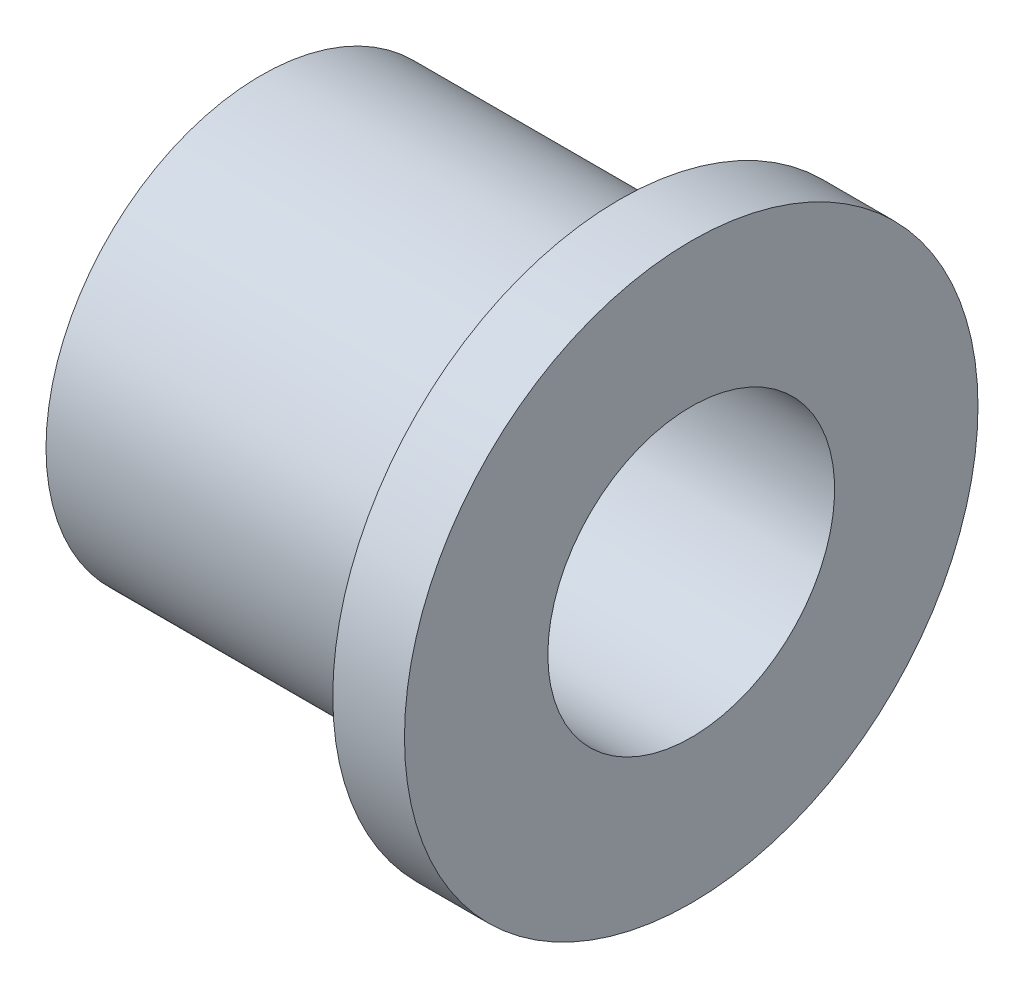
SolidWorks part; units mm, degrees
ref_plane "Front Plane" through (0, 0, 0) normal (0, 0, 1) x (1, 0, 0)
ref_plane "Top Plane" through (0, 0, 0) normal (0, 1, 0) x (1, 0, 0)
ref_plane "Right Plane" through (0, 0, 0) normal (1, 0, 0) x (0, 0, -1)
sketch "Sketch1" plane through (0, 0, 0) normal (0, 1, 0) x (1, 0, 0)
  line L0 (0, 4) -> (0, 6)
  line L1 (0, 6) -> (10, 6)
  line L2 (10, 6) -> (10, 8)
  line L3 (10, 8) -> (12, 8)
  line L4 (12, 8) -> (12, 4)
  line L5 (12, 4) -> (0, 4)
  line L6 (0, 0) -> (3.6529, 0) construction
  dimension "D1" = 4
  dimension "D2" = 6
  dimension "D3" = 12
  dimension "D4" = 2
  dimension "D5" = 8
revolve "Revolve1" add sketch "Sketch1" angle 360 about L6
